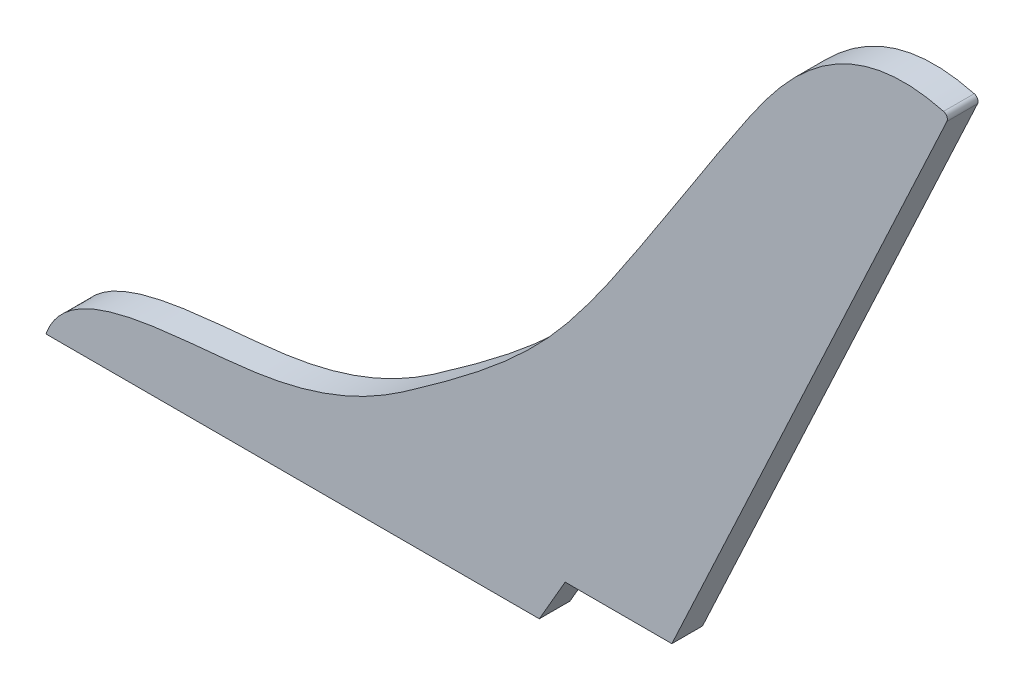
SolidWorks part; units mm, degrees
ref_plane "Front Plane" through (0, 0, 0) normal (0, 0, 1) x (1, 0, 0)
ref_plane "Top Plane" through (0, 0, 0) normal (0, 1, 0) x (1, 0, 0)
ref_plane "Right Plane" through (0, 0, 0) normal (1, 0, 0) x (0, 0, -1)
sketch "Sketch1" plane through (0, 0, 0) normal (0, 0, 1) x (1, 0, 0)
  line L0 (0, 0) -> (2453.64, 0)
  line L1 (3112.9178, 222.504) -> (4493.361, 3182.874)
  line L2 (2453.64, 0) -> (2582.1027, 222.504)
  line L3 (2582.1027, 222.504) -> (3112.9178, 222.504)
  spline S0 degree 3 poles (0, 0) (116.9988, 333.5734) (1063.48, 273.484) (1615.6058, 525.977) (2074.6663, 847.0329) (2399.4764, 1097.3889) (2745.9243, 1535.7924) (2889.3333, 1753.3693) (3207.9045, 2236.5674) (3278.555, 2366.3178) (3948.7478, 3347.0887) (4493.361, 3182.874) knots 0 0 0 0 0.132157 0.223214 0.257951 0.454915 0.494597 0.615089 0.65376 0.842637 1 1 1 1
  dimension "D1" = 3182.874
  dimension "D2" = 120
  dimension "D3" = 115
  dimension "D4" = 222.504
  dimension "D5" = 2453.64
extrude "Boss-Extrude1" add sketch "Sketch1" along normal blind 152.4
fillet "Fillet1" radius 25.4 1 edges at (4493.361, 3182.874, 76.2)
